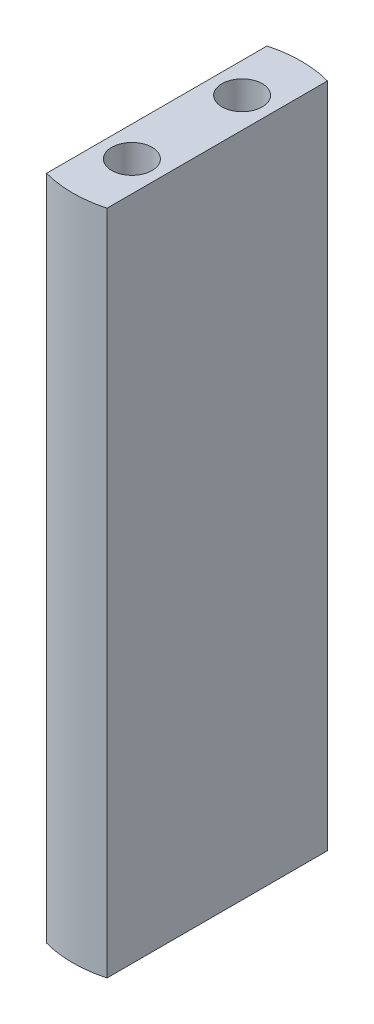
SolidWorks part; units mm, degrees
ref_plane "Front Plane" through (0, 0, 0) normal (0, 0, 1) x (1, 0, 0)
ref_plane "Top Plane" through (0, 0, 0) normal (0, 1, 0) x (1, 0, 0)
ref_plane "Right Plane" through (0, 0, 0) normal (1, 0, 0) x (0, 0, -1)
sketch "Sketch2" plane through (0, 0, 0) normal (0, 1, 0) x (1, 0, 0)
  line L0 (9.525, 0) -> (9.525, 34.7171)
  line L2 (9.525, 34.7171) -> (9.525, -34.7171)
  line L4 (-9.525, 34.7171) -> (-9.525, -34.7171)
  line L7 (9.525, 0) -> (-9.525, 0) construction
  arc A0 (-9.525, -34.7171) -> (9.525, -34.7171) centre (0, 0) ccw
  arc A1 (9.525, 34.7171) -> (-9.525, 34.7171) centre (0, 0) ccw
  circle A2 centre (0, 17.3585) radius 6.35
  circle A3 centre (0, -17.3585) radius 6.35
  point P9 (9.525, 17.3585)
  dimension "D1" = 72
  dimension "D3" = 12.7
  dimension "D2" = 19.05
extrude "Boss-Extrude1" add sketch "Sketch2" along normal blind 210 contours L2 L7 L4 A0 A3 | L7 L0 A1 L4 A2
equation "\"grueso tornillo\"=12.7"
equation "\"D3@Sketch2\"=\"grueso tornillo\""
equation "\"grueso tabla\"=19.05"
equation "\"D2@Sketch2\"=\"grueso tabla\""
